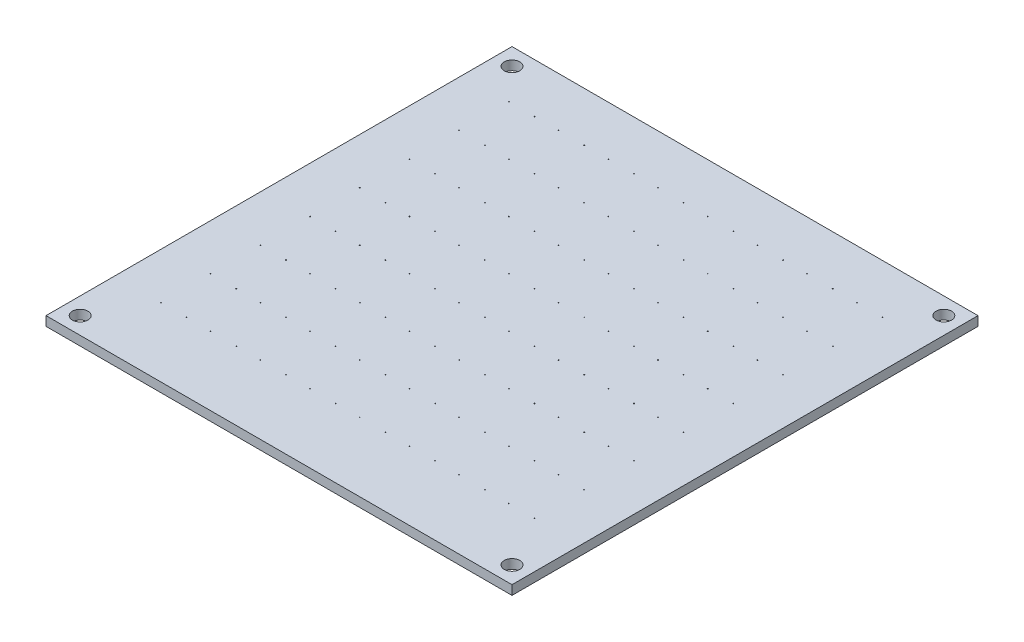
SolidWorks part; units mm, degrees
material "Mogno"
ref_plane "Plano frontal" through (0, 0, 0) normal (0, 0, 1) x (1, 0, 0)
ref_plane "Plano superior" through (0, 0, 0) normal (0, 1, 0) x (1, 0, 0)
ref_plane "Plano direito" through (0, 0, 0) normal (1, 0, 0) x (0, 0, -1)
sketch "Esboço1" plane through (0, 0, 0) normal (0, 1, 0) x (1, 0, 0)
  line L1 (-150, 150) -> (150, 150)
  line L2 (-150, 150) -> (-150, -150)
  line L3 (-150, -150) -> (150, -150)
  line L4 (150, 150) -> (150, -150)
  line L5 (-150, 150) -> (150, -150) construction
  line L6 (-150, -150) -> (150, 150) construction
  point P0 (0, 0)
  dimension "D1" = 300
extrude "Ressalto-extrusão1" add sketch "Esboço1" along normal blind 6
sketch "Esboço2" plane through (0, 6, 0) normal (0, 1, 0) x (1, 0, 0)
  line L0 (-150, 150) -> (-150, -150) construction
  line L1 (-139, 139) -> (139, 139) construction
  line L2 (-139, 139) -> (-139, -139) construction
  line L3 (-139, -139) -> (139, -139) construction
  line L4 (139, 139) -> (139, -139) construction
  line L5 (-139, 139) -> (139, -139) construction
  line L6 (-139, -139) -> (139, 139) construction
  circle A0 centre (-139, 139) radius 5
  circle A1 centre (139, 139) radius 5
  circle A2 centre (139, -139) radius 5
  circle A3 centre (-139, -139) radius 5
  point P0 (0, 0)
  dimension "D2" = 10
  dimension "D1" = 11
extrude "Corte-extrusão1" cut sketch "Esboço2" against normal through all
sketch "Esboço3" plane through (0, 6, 0) normal (0, 1, 0) x (1, 0, 0)
  line L0 (-96, 128) -> (-96, -128) construction
  line L1 (-128, 128) -> (128, 128) construction
  line L2 (-128, 128) -> (-128, -128) construction
  line L3 (-128, -128) -> (128, -128) construction
  line L4 (128, 128) -> (128, -128) construction
  line L5 (-128, 128) -> (128, -128) construction
  line L6 (-128, -128) -> (128, 128) construction
  line L7 (-64, 128) -> (-64, -128) construction
  line L8 (-32, 128) -> (-32, -128) construction
  line L9 (0, 128) -> (0, -128) construction
  line L10 (32, 128) -> (32, -128) construction
  line L11 (64, 128) -> (64, -128) construction
  line L12 (96, 128) -> (96, -128) construction
  line L13 (-128, 96) -> (128, 96) construction
  line L14 (-112, 112) -> (-112, 128) construction
  line L15 (-112, 112) -> (-128, 112) construction
  line L16 (-103.75, 118) -> (-103.75, 112) construction
  line L17 (-103.75, 112) -> (-112, 112) construction
  line L18 (-128, 64) -> (128, 64) construction
  line L19 (-128, 0) -> (128, 0) construction
  line L20 (-128, 32) -> (128, 32) construction
  line L21 (-128, -96) -> (128, -96) construction
  line L22 (-128, -64) -> (128, -64) construction
  line L23 (-128, -32) -> (128, -32) construction
  circle A0 centre (-112, 112) radius 12.5 construction
  circle A1 centre (-103.75, 118.25) radius 0.25
  circle A2 centre (-120.25, 118.25) radius 0.25
  circle A3 centre (-88.25, 118.25) radius 0.25
  circle A4 centre (-71.75, 118.25) radius 0.25
  circle A5 centre (-56.25, 118.25) radius 0.25
  circle A6 centre (-39.75, 118.25) radius 0.25
  circle A7 centre (-24.25, 118.25) radius 0.25
  circle A8 centre (-7.75, 118.25) radius 0.25
  circle A9 centre (7.75, 118.25) radius 0.25
  circle A10 centre (24.25, 118.25) radius 0.25
  circle A11 centre (39.75, 118.25) radius 0.25
  circle A12 centre (56.25, 118.25) radius 0.25
  circle A13 centre (71.75, 118.25) radius 0.25
  circle A14 centre (88.25, 118.25) radius 0.25
  circle A15 centre (103.75, 118.25) radius 0.25
  circle A16 centre (120.25, 118.25) radius 0.25
  circle A17 centre (71.75, 86.25) radius 0.25
  circle A18 centre (-103.75, 86.25) radius 0.25
  circle A19 centre (24.25, 86.25) radius 0.25
  circle A20 centre (-7.75, 86.25) radius 0.25
  circle A21 centre (103.75, 86.25) radius 0.25
  circle A22 centre (-71.75, 86.25) radius 0.25
  circle A23 centre (120.25, 86.25) radius 0.25
  circle A24 centre (-56.25, 86.25) radius 0.25
  circle A25 centre (88.25, 86.25) radius 0.25
  circle A26 centre (39.75, 86.25) radius 0.25
  circle A27 centre (-120.25, 86.25) radius 0.25
  circle A28 centre (-39.75, 86.25) radius 0.25
  circle A29 centre (56.25, 86.25) radius 0.25
  circle A30 centre (-88.25, 86.25) radius 0.25
  circle A31 centre (-24.25, 86.25) radius 0.25
  circle A32 centre (7.75, 86.25) radius 0.25
  circle A33 centre (71.75, 54.25) radius 0.25
  circle A34 centre (-71.75, 54.25) radius 0.25
  circle A35 centre (88.25, 54.25) radius 0.25
  circle A36 centre (-88.25, 54.25) radius 0.25
  circle A37 centre (-24.25, 54.25) radius 0.25
  circle A38 centre (103.75, 54.25) radius 0.25
  circle A39 centre (39.75, 54.25) radius 0.25
  circle A40 centre (56.25, 54.25) radius 0.25
  circle A41 centre (7.75, 54.25) radius 0.25
  circle A42 centre (-120.25, 54.25) radius 0.25
  circle A43 centre (-103.75, 54.25) radius 0.25
  circle A44 centre (120.25, 54.25) radius 0.25
  circle A45 centre (-56.25, 54.25) radius 0.25
  circle A46 centre (-39.75, 54.25) radius 0.25
  circle A47 centre (24.25, 54.25) radius 0.25
  circle A48 centre (-7.75, 54.25) radius 0.25
  circle A49 centre (-120.25, 22.25) radius 0.25
  circle A50 centre (-56.25, 22.25) radius 0.25
  circle A51 centre (-24.25, 22.25) radius 0.25
  circle A52 centre (88.25, 22.25) radius 0.25
  circle A53 centre (-103.75, 22.25) radius 0.25
  circle A54 centre (-88.25, 22.25) radius 0.25
  circle A55 centre (-7.75, 22.25) radius 0.25
  circle A56 centre (24.25, 22.25) radius 0.25
  circle A57 centre (71.75, 22.25) radius 0.25
  circle A58 centre (-71.75, 22.25) radius 0.25
  circle A59 centre (-39.75, 22.25) radius 0.25
  circle A60 centre (56.25, 22.25) radius 0.25
  circle A61 centre (39.75, 22.25) radius 0.25
  circle A62 centre (120.25, 22.25) radius 0.25
  circle A63 centre (103.75, 22.25) radius 0.25
  circle A64 centre (7.75, 22.25) radius 0.25
  circle A65 centre (7.75, -9.75) radius 0.25
  circle A66 centre (-71.75, -9.75) radius 0.25
  circle A67 centre (39.75, -9.75) radius 0.25
  circle A68 centre (-88.25, -9.75) radius 0.25
  circle A69 centre (24.25, -9.75) radius 0.25
  circle A70 centre (-39.75, -9.75) radius 0.25
  circle A71 centre (-56.25, -9.75) radius 0.25
  circle A72 centre (-103.75, -9.75) radius 0.25
  circle A73 centre (-24.25, -9.75) radius 0.25
  circle A74 centre (71.75, -9.75) radius 0.25
  circle A75 centre (88.25, -9.75) radius 0.25
  circle A76 centre (-120.25, -9.75) radius 0.25
  circle A77 centre (-7.75, -9.75) radius 0.25
  circle A78 centre (56.25, -9.75) radius 0.25
  circle A79 centre (103.75, -9.75) radius 0.25
  circle A80 centre (120.25, -9.75) radius 0.25
  circle A81 centre (-103.75, -41.75) radius 0.25
  circle A82 centre (-120.25, -41.75) radius 0.25
  circle A83 centre (-56.25, -41.75) radius 0.25
  circle A84 centre (71.75, -41.75) radius 0.25
  circle A85 centre (120.25, -41.75) radius 0.25
  circle A86 centre (103.75, -41.75) radius 0.25
  circle A87 centre (88.25, -41.75) radius 0.25
  circle A88 centre (-88.25, -41.75) radius 0.25
  circle A89 centre (-7.75, -41.75) radius 0.25
  circle A90 centre (-71.75, -41.75) radius 0.25
  circle A91 centre (24.25, -41.75) radius 0.25
  circle A92 centre (39.75, -41.75) radius 0.25
  circle A93 centre (-39.75, -41.75) radius 0.25
  circle A94 centre (7.75, -41.75) radius 0.25
  circle A95 centre (56.25, -41.75) radius 0.25
  circle A96 centre (-24.25, -41.75) radius 0.25
  circle A97 centre (71.75, -105.75) radius 0.25
  circle A98 centre (-71.75, -105.75) radius 0.25
  circle A99 centre (-56.25, -73.75) radius 0.25
  circle A100 centre (-7.75, -73.75) radius 0.25
  circle A101 centre (-7.75, -105.75) radius 0.25
  circle A102 centre (39.75, -105.75) radius 0.25
  circle A103 centre (-24.25, -73.75) radius 0.25
  circle A104 centre (-120.25, -73.75) radius 0.25
  circle A105 centre (120.25, -73.75) radius 0.25
  circle A106 centre (56.25, -73.75) radius 0.25
  circle A107 centre (88.25, -105.75) radius 0.25
  circle A108 centre (7.75, -105.75) radius 0.25
  circle A109 centre (71.75, -73.75) radius 0.25
  circle A110 centre (103.75, -105.75) radius 0.25
  circle A111 centre (-39.75, -73.75) radius 0.25
  circle A112 centre (-120.25, -105.75) radius 0.25
  circle A113 centre (56.25, -105.75) radius 0.25
  circle A114 centre (7.75, -73.75) radius 0.25
  circle A115 centre (88.25, -73.75) radius 0.25
  circle A116 centre (-24.25, -105.75) radius 0.25
  circle A117 centre (-71.75, -73.75) radius 0.25
  circle A118 centre (120.25, -105.75) radius 0.25
  circle A119 centre (39.75, -73.75) radius 0.25
  circle A120 centre (-56.25, -105.75) radius 0.25
  circle A121 centre (-103.75, -105.75) radius 0.25
  circle A122 centre (-103.75, -73.75) radius 0.25
  circle A123 centre (-88.25, -105.75) radius 0.25
  circle A124 centre (24.25, -105.75) radius 0.25
  circle A125 centre (-88.25, -73.75) radius 0.25
  circle A126 centre (103.75, -73.75) radius 0.25
  circle A127 centre (24.25, -73.75) radius 0.25
  circle A128 centre (-39.75, -105.75) radius 0.25
  point P0 (0, 0)
  dimension "D4" = 25
  dimension "D9" = 0.5
  dimension "D1" = 256
  dimension "D2" = 32
  dimension "D3" = 32
  dimension "D5" = 16
  dimension "D6" = 16
  dimension "D7" = 8.25
  dimension "D8" = 6
extrude "Corte-extrusão3" cut sketch "Esboço3" against normal through all
